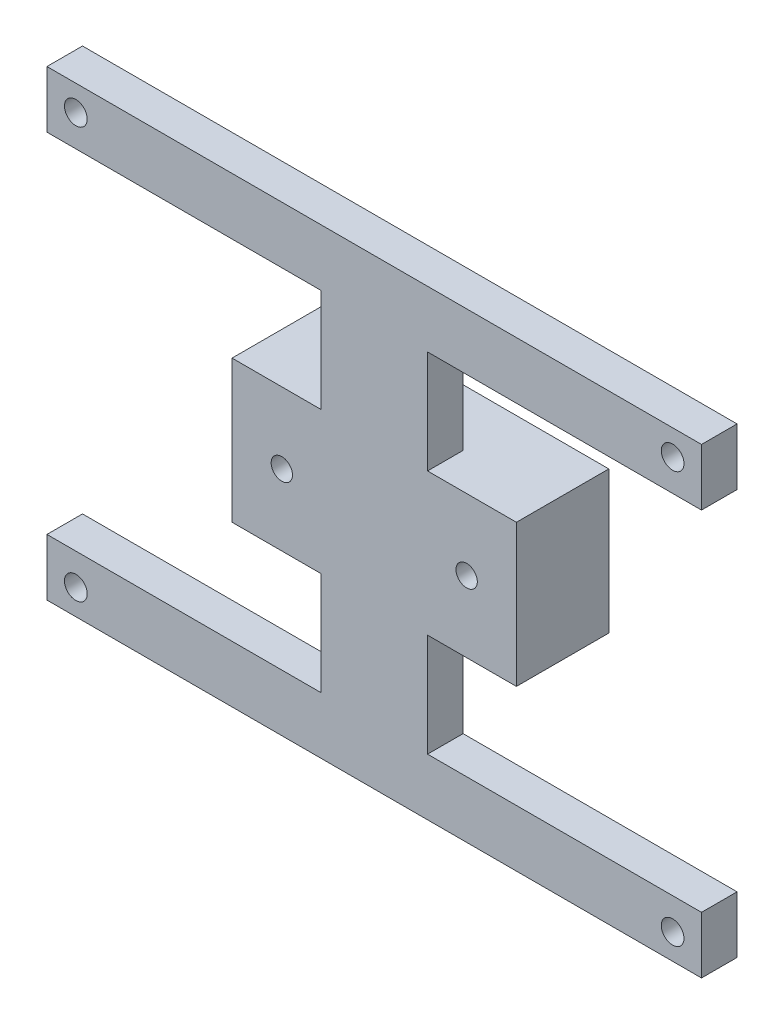
SolidWorks part; units mm, degrees
ref_plane "前视基准面" through (0, 0, 0) normal (0, 0, 1) x (1, 0, 0)
ref_plane "上视基准面" through (0, 0, 0) normal (0, 1, 0) x (1, 0, 0)
ref_plane "右视基准面" through (0, 0, 0) normal (1, 0, 0) x (0, 0, -1)
other "Configuration Table"
sketch "草图1" plane through (0, 0, 0) normal (0, 0, 1) x (1, 0, 0)
  line L0 (46.0375, -32.5) -> (46.0375, 32.5) construction
  line L1 (-46.0375, 32.5) -> (46.0375, 32.5)
  line L2 (-46.0375, 32.5) -> (-46.0375, 24.5)
  line L3 (-46.0375, 24.5) -> (46.0375, 24.5)
  line L4 (46.0375, 32.5) -> (46.0375, 24.5)
  line L5 (-46.0375, -32.5) -> (-46.0375, 32.5) construction
  line L6 (46.0375, -32.5) -> (-46.0375, -32.5)
  line L7 (46.0375, -32.5) -> (46.0375, -24.5)
  line L8 (46.0375, -24.5) -> (-46.0375, -24.5)
  line L9 (-46.0375, -32.5) -> (-46.0375, -24.5)
  line L10 (0, 24.5) -> (0, -24.5) construction
  line L15 (-7.5, 0) -> (7.5, 0) construction
  line L16 (-7.5, -24.5) -> (7.5, -24.5)
  line L17 (-7.5, -24.5) -> (-7.5, 24.5)
  line L18 (-7.5, 24.5) -> (7.5, 24.5)
  line L19 (7.5, -24.5) -> (7.5, 24.5)
  line L20 (-7.5, -24.5) -> (7.5, 24.5) construction
  line L21 (-7.5, 24.5) -> (7.5, -24.5) construction
  line L23 (-20, -10) -> (20, -10)
  line L24 (-20, -10) -> (-20, 10)
  line L25 (-20, 10) -> (20, 10)
  line L26 (20, -10) -> (20, 10)
  line L27 (-20, -10) -> (20, 10) construction
  line L28 (-20, 10) -> (20, -10) construction
  circle A0 centre (-41.9735, 28.92) radius 1.6
  circle A1 centre (41.9735, 28.92) radius 1.6
  circle A2 centre (41.9735, -28.92) radius 1.6
  circle A3 centre (-41.9735, -28.92) radius 1.6
  point P28 (0, 0)
  point P36 (0, 0)
  dimension "D3" = 3.2
  dimension "D4" = 3.2
  dimension "D5" = 3.2
  dimension "D6" = 3.2
  dimension "D1" = 8
  dimension "D2" = 8
  dimension "D7" = 15
  dimension "D8" = 20
  dimension "D9" = 40
extrude "凸台-拉伸1" add sketch "草图1" along normal blind 5 contours L4 L1 L2 L3 A1 A0 | L23 L26 L25 L19 | L25 L17 L23 L19 | L25 L24 L23 L17 | L17 L25 L19 L3 | L9 L6 L7 L8 A3 A2 | L23 L17 L8 L19
sketch "草图2" plane through (0, 0, 5) normal (0, 0, 1) x (1, 0, 0)
  line L0 (-20, 0) -> (20, 0) construction
  line L1 (-20, -10) -> (-20, 10) construction
  line L2 (20, -10) -> (20, 10) construction
  circle A0 centre (13, 0) radius 1.5
  circle A1 centre (-13, 0) radius 1.5
  dimension "D1" = 3
  dimension "D2" = 3
  dimension "D3" = 7
  dimension "D4" = 7
extrude "切除-拉伸1" cut sketch "草图2" against normal blind 10
sketch "草图4" plane through (0, 0, 0) normal (0, 0, -1) x (-1, 0, 0)
  line L1 (-20, 10) -> (20, 10)
  line L2 (-20, 10) -> (-20, -10)
  line L3 (-20, -10) -> (20, -10)
  line L4 (20, 10) -> (20, -10)
  circle A0 centre (-13, 0) radius 1.5
  circle A1 centre (13, 0) radius 1.5
extrude "凸台-拉伸3" add sketch "草图4" along normal blind 8
